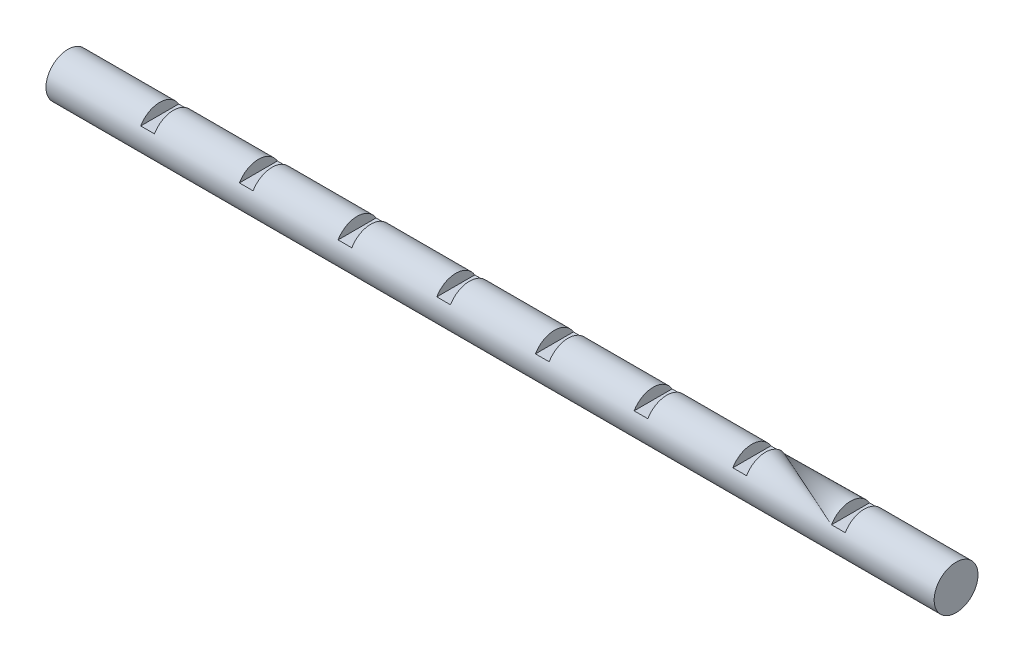
SolidWorks part; units mm, degrees
ref_plane "Front Plane" through (0, 0, 0) normal (0, 0, 1) x (1, 0, 0)
ref_plane "Top Plane" through (0, 0, 0) normal (0, 1, 0) x (1, 0, 0)
ref_plane "Right Plane" through (0, 0, 0) normal (1, 0, 0) x (0, 0, -1)
sketch "Sketch2" plane through (0, 0, 0) normal (1, 0, 0) x (0, 0, -1)
  circle A0 centre (0, 0) radius 4
  dimension "D1" = 8
extrude "Boss-Extrude1" add sketch "Sketch2" along normal mid plane 162
sketch "Sketch3" plane through (0, 0, 0) normal (0, 1, 0) x (1, 0, 0)
  line L0 (-81, 0) -> (81, 0) construction
  line L1 (-81, 4) -> (-81, -4) construction
  line L2 (81, -4) -> (81, 4) construction
  line L3 (81, 4) -> (-81, 4) construction
  line L4 (-64.25, 4) -> (-61.75, 4)
  line L5 (-64.25, 4) -> (-64.25, -4)
  line L6 (-64.25, -4) -> (-61.75, -4)
  line L7 (-61.75, 4) -> (-61.75, -4)
  line L8 (-64.25, 4) -> (-61.75, -4) construction
  line L9 (-64.25, -4) -> (-61.75, 4) construction
  line L10 (-46.25, 4) -> (-46.25, -4)
  line L11 (-46.25, 4) -> (-43.75, 4)
  line L12 (-43.75, 4) -> (-43.75, -4)
  line L13 (-46.25, -4) -> (-43.75, -4)
  line L14 (-28.25, 4) -> (-28.25, -4)
  line L15 (-28.25, 4) -> (-25.75, 4)
  line L16 (-25.75, 4) -> (-25.75, -4)
  line L17 (-28.25, -4) -> (-25.75, -4)
  line L18 (-10.25, 4) -> (-10.25, -4)
  line L19 (-10.25, 4) -> (-7.75, 4)
  line L20 (-7.75, 4) -> (-7.75, -4)
  line L21 (-10.25, -4) -> (-7.75, -4)
  line L22 (7.75, 4) -> (7.75, -4)
  line L23 (7.75, 4) -> (10.25, 4)
  line L24 (10.25, 4) -> (10.25, -4)
  line L25 (7.75, -4) -> (10.25, -4)
  line L26 (25.75, 4) -> (25.75, -4)
  line L27 (25.75, 4) -> (28.25, 4)
  line L28 (28.25, 4) -> (28.25, -4)
  line L29 (25.75, -4) -> (28.25, -4)
  line L30 (43.75, 4) -> (43.75, -4)
  line L31 (43.75, 4) -> (46.25, 4)
  line L32 (46.25, 4) -> (46.25, -4)
  line L33 (43.75, -4) -> (46.25, -4)
  line L34 (61.75, 4) -> (61.75, -4)
  line L35 (61.75, 4) -> (64.25, 4)
  line L36 (64.25, 4) -> (64.25, -4)
  line L37 (61.75, -4) -> (64.25, -4)
  point P6 (-63, 0)
  dimension "D1" = 18
  dimension "D2" = 2.5
  dimension "D3" = 8
extrude "Cut-Extrude1" cut sketch "Sketch3" along normal blind 10 from offset 2
